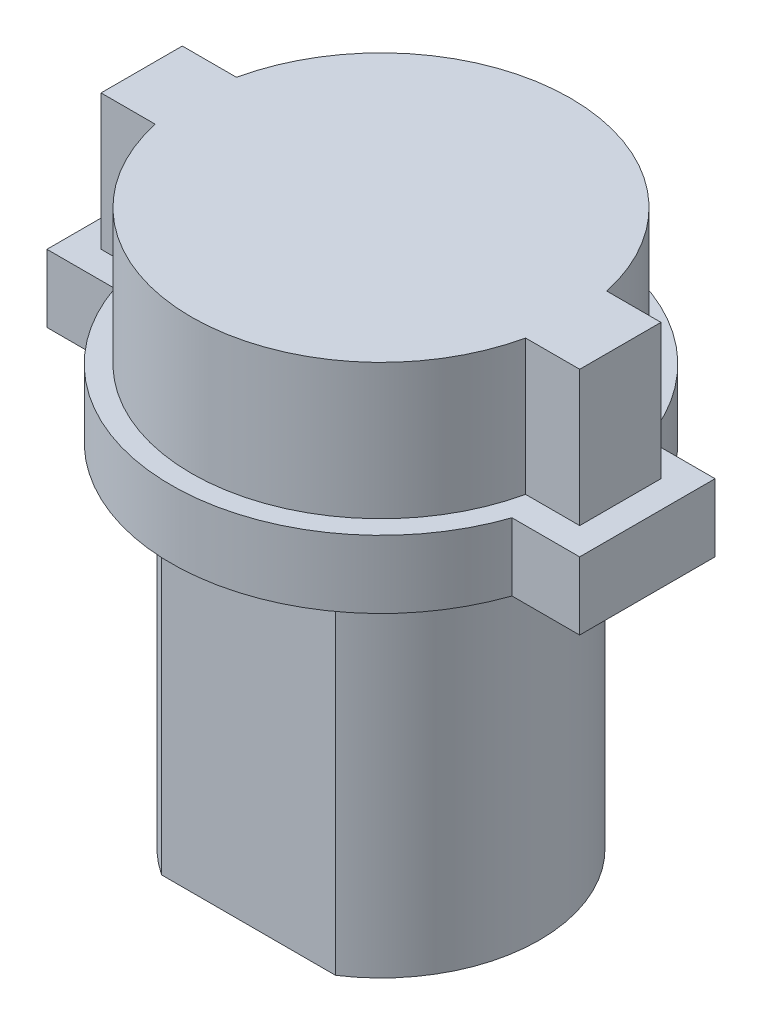
SolidWorks part; units mm, degrees
ref_plane "Front Plane" through (0, 0, 0) normal (0, 0, 1) x (1, 0, 0)
ref_plane "Top Plane" through (0, 0, 0) normal (0, 1, 0) x (1, 0, 0)
ref_plane "Right Plane" through (0, 0, 0) normal (1, 0, 0) x (0, 0, -1)
sketch "Sketch1" plane through (0, 0, 0) normal (0, 1, 0) x (1, 0, 0)
  line L0 (3.211, 4.89) -> (-3.211, 4.89)
  line L1 (-5.85, 0) -> (5.85, 0) construction
  line L2 (3.211, -4.89) -> (-3.211, -4.89)
  circle A0 centre (0, 0) radius 5.85
  dimension "D1" = 11.7
  dimension "D2" = 9.78
extrude "Boss-Extrude1" add sketch "Sketch1" along normal blind 13 contours A0 L1 L0 | L1 A0 L2
sketch "Sketch2" plane through (0, 13, 0) normal (0, 1, 0) x (1, 0, 0)
  line L0 (0, 7.75) -> (0, -7.75) construction
  line L1 (-7.3357, -2.5) -> (-9.8357, -2.5)
  line L2 (-9.8357, -2.5) -> (-9.8357, 2.5)
  line L3 (-9.8357, 2.5) -> (-7.3357, 2.5)
  line L11 (9.8357, 2.5) -> (7.3357, 2.5)
  line L12 (9.8357, -2.5) -> (9.8357, 2.5)
  line L13 (7.3357, -2.5) -> (9.8357, -2.5)
  circle A0 centre (0, 0) radius 7.75
  point P5 (9.8357, 0)
  arc M5 (-3.211, 4.89) -> (-3.211, -4.89) centre (0, 0) ccw
  line M6 (-3.211, -4.89) -> (3.211, -4.89)
  arc M7 (3.211, -4.89) -> (3.211, 4.89) centre (0, 0) ccw
  line M8 (3.211, 4.89) -> (-3.211, 4.89)
  dimension "D1" = 15.5
  dimension "D2" = 2.5
  dimension "D3" = 5
extrude "Boss-Extrude2" add sketch "Sketch2" along normal blind 2.5 contours L0 A0 M6 M5 M8 | A0 L0 M8 M7 M6 | L0 M8 M6 M7 | A0 L13 L12 L11 | L0 M8 M5 M6 | A0 L3 L2 L1
sketch "Sketch3" plane through (0, 15.5, 0) normal (0, 1, 0) x (1, 0, 0)
  line L0 (-1.5, 6.8374) -> (-1.5, 8.8374)
  line L1 (-1.5, 8.8374) -> (1.5, 8.8374)
  line L2 (1.5, 8.8374) -> (1.5, 6.8374)
  line L3 (0, 0) -> (4.9497, 4.9497) construction
  line L4 (-6.8374, -1.5) -> (-8.8374, -1.5)
  line L5 (-8.8374, -1.5) -> (-8.8374, 1.5)
  line L6 (-7, 0) -> (7, 0) construction
  line L7 (-1.5, -6.8374) -> (-1.5, -8.8374)
  line L8 (-1.5, -8.8374) -> (1.5, -8.8374)
  line L9 (1.5, -8.8374) -> (1.5, -6.8374)
  line L10 (-8.8374, 1.5) -> (-6.8374, 1.5)
  line L11 (8.8374, 1.5) -> (6.8374, 1.5)
  line L12 (6.8374, -1.5) -> (8.8374, -1.5)
  line L13 (8.8374, -1.5) -> (8.8374, 1.5)
  circle A2 centre (0, 0) radius 7
  point P6 (0, -8.8374)
  dimension "D1" = 14
  dimension "D2" = 3
  dimension "D3" = 2
  dimension "D4" = 45
extrude "Boss-Extrude3" add sketch "Sketch3" along normal blind 5 contours A2 | A2 L10 L5 L4 | A2 L12 L13 L11
